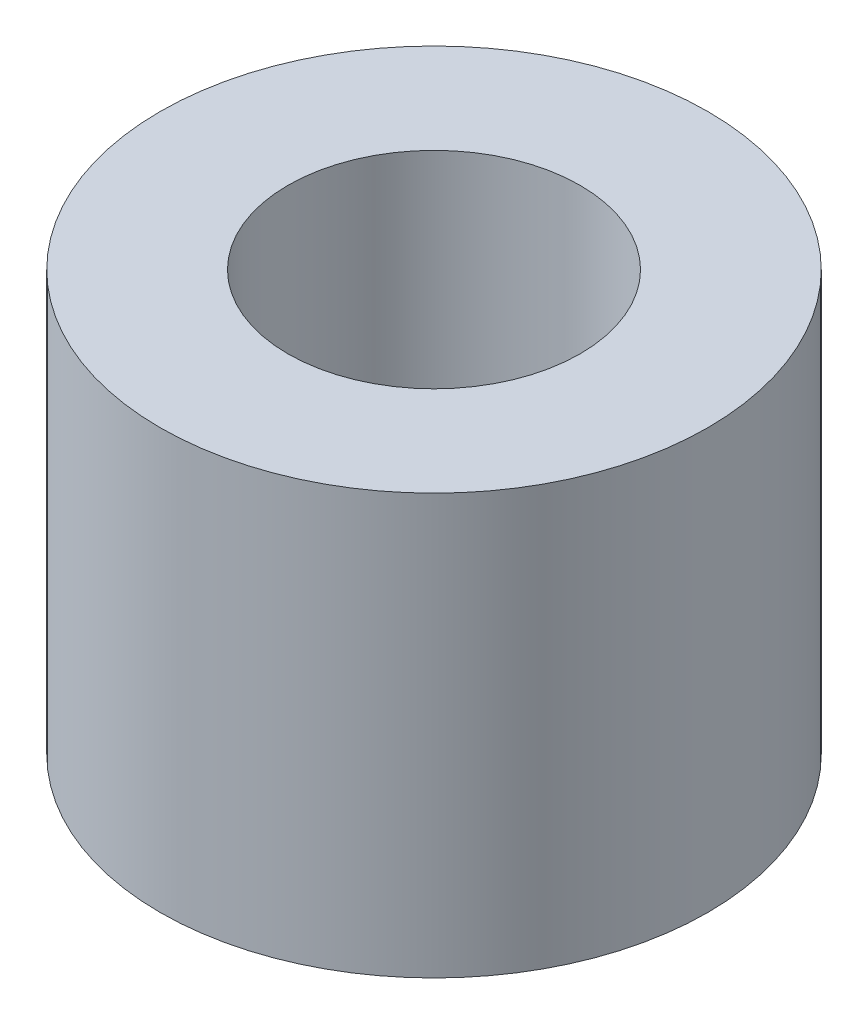
SolidWorks part; units mm, degrees
material "6063-T5"
ref_plane "Alzado" through (0, 0, 0) normal (0, 0, 1) x (1, 0, 0)
ref_plane "Planta" through (0, 0, 0) normal (0, 1, 0) x (1, 0, 0)
ref_plane "Vista lateral" through (0, 0, 0) normal (1, 0, 0) x (0, 0, -1)
ref_plane "Plano1" through (0, 0, 0) normal (0, -1, 0) x (1, 0, 0)
sketch "Croquis1" plane through (0, 0, 0) normal (0, -1, 0) x (1, 0, 0)
  circle A0 centre (0, 0) radius 1.6
  circle A1 centre (0, 0) radius 3
  dimension "D1" = 3.2
  dimension "D2" = 6
extrude "Saliente-Extruir1" add sketch "Croquis1" against normal blind 4.6
equation "\"L\"= 1"
